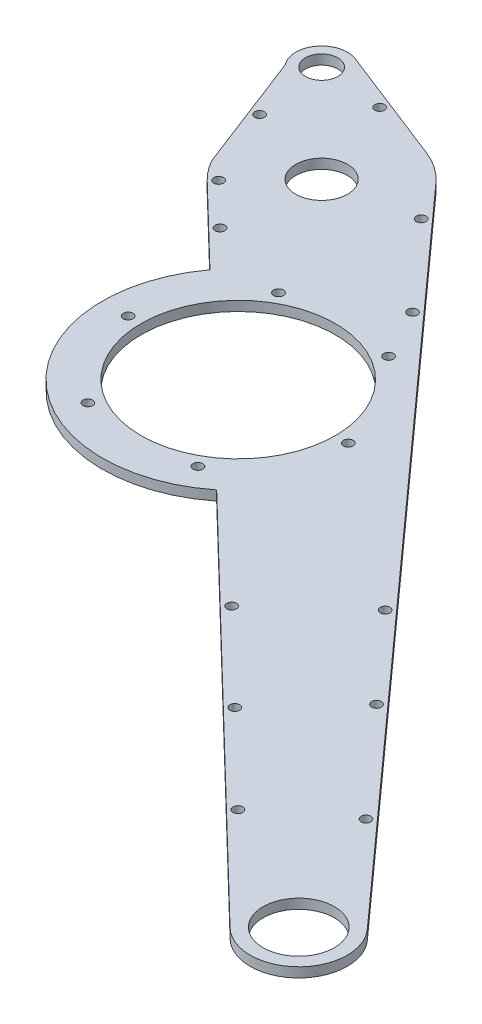
SolidWorks part; units mm, degrees
material "Zoltek Panex 33"
ref_plane "前视基准面" through (0, 0, 0) normal (0, 0, 1) x (1, 0, 0)
ref_plane "上视基准面" through (0, 0, 0) normal (0, 1, 0) x (1, 0, 0)
ref_plane "右视基准面" through (0, 0, 0) normal (1, 0, 0) x (0, 0, -1)
sketch "Sketch1" plane through (0, 0, 0) normal (0, 1, 0) x (1, 0, 0)
  line L0 (-30, 30) -> (0, 0) construction
  line L1 (-36.245, 25) -> (-22, -11.8743)
  line L2 (-27.0838, 37.4495) -> (9.1132, 23.2798)
  line L3 (-17.3624, -17.9874) -> (186.1101, -214.3899)
  line L4 (18.5896, 16.7161) -> (207.6813, -193.5678)
  circle A0 centre (0, 0) radius 25
  circle A1 centre (0, 0) radius 8
  circle A2 centre (-30, 30) radius 8
  circle A3 centre (-30, 30) radius 5
  circle A4 centre (196.5275, -203.5975) radius 15
  circle A5 centre (196.5275, -203.5975) radius 11
  circle A16 centre (40.6989, -66.4645) radius 30
  circle A18 centre (6.6989, -66.4645) radius 1.5
  circle A19 centre (23.6989, -37.0196) radius 1.5
  circle A20 centre (57.6989, -37.0196) radius 1.5
  circle A21 centre (74.6989, -66.4645) radius 1.5
  circle A22 centre (57.6989, -95.9094) radius 1.5
  circle A23 centre (23.6989, -95.9094) radius 1.5
  arc A26 (59.711, -29.014) -> (79.9512, -51.5225) centre (40.6989, -66.4645) ccw
  point P24 (0, 0)
  point P37 (40.6989, -66.4645)
  point P38 (40.6989, -66.4645)
  dimension "D1" = 6
extrude "Boss-Extrude1" add sketch "Sketch1" along normal blind 3
sketch "Sketch2" plane through (0, 3, 0) normal (0, 1, 0) x (1, 0, 0)
  line L13 (0, 0) -> (196.5275, -203.5975) construction
  circle A80 centre (0, 0) radius 8
  circle A100 centre (-15.6262, -16.1887) radius 1.5
  circle A101 centre (-2.6565, -28.7076) radius 1.5
  circle A105 centre (127.8834, -154.7118) radius 1.5
  circle A106 centre (100.2687, -128.0566) radius 1.5
  circle A107 centre (155.7005, -181.5623) radius 1.5
  circle A108 centre (148.935, -131.9765) radius 1.5
  circle A109 centre (177.9939, -164.2922) radius 1.5
  circle A110 centre (125.057, -105.4225) radius 1.5
  circle A111 centre (49.601, -21.5098) radius 1.5
  circle A112 centre (25.9486, 4.7935) radius 1.5
  circle A113 centre (-26.896, 7.7368) radius 1.5
  circle A114 centre (-10.2722, 28.1837) radius 1.5
extrude "Cut-Extrude1" cut sketch "Sketch2" against normal blind 10
